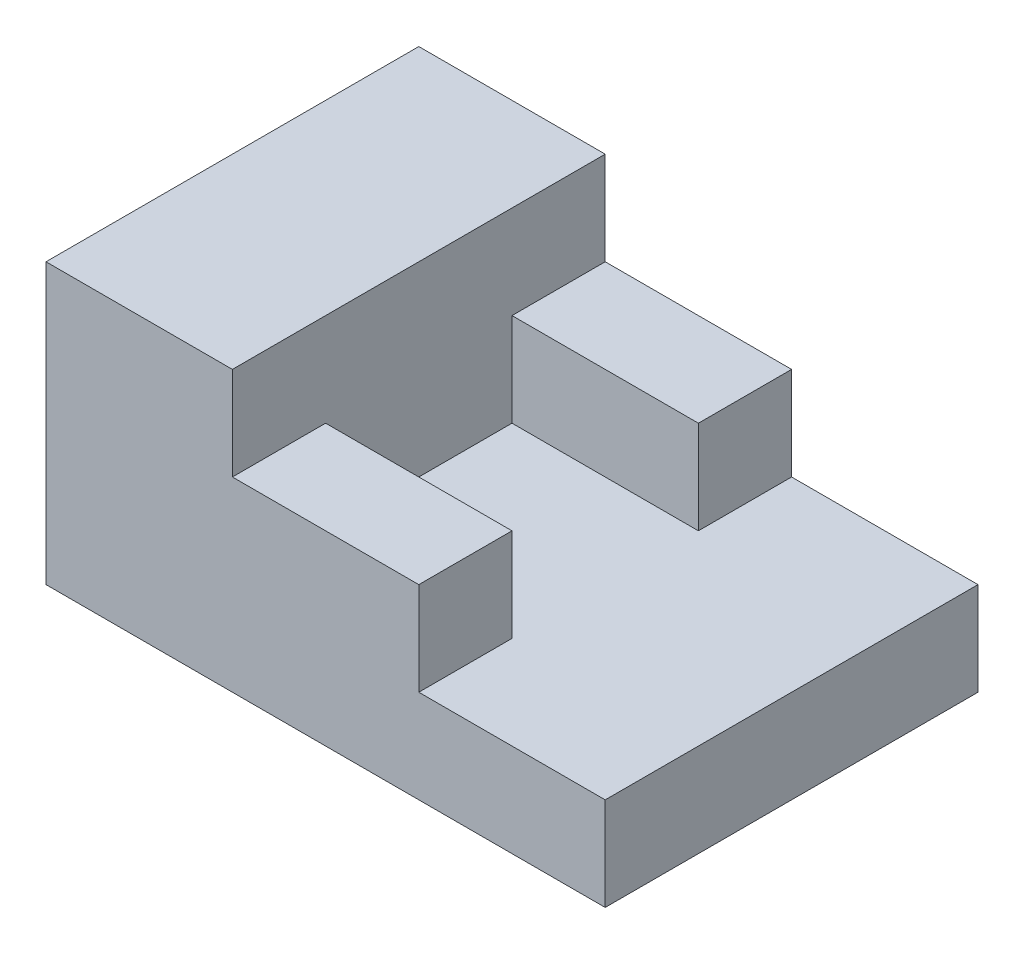
SolidWorks part; units mm, degrees
ref_plane "前基準面" through (0, 0, 0) normal (0, 0, 1) x (1, 0, 0)
ref_plane "上基準面" through (0, 0, 0) normal (0, 1, 0) x (1, 0, 0)
ref_plane "右基準面" through (0, 0, 0) normal (1, 0, 0) x (0, 0, -1)
sketch "草圖1" plane through (0, 0, 0) normal (0, 0, 1) x (1, 0, 0)
  line L0 (0, 0) -> (0, 10)
  line L1 (0, 10) -> (-20, 10)
  line L2 (-20, 10) -> (-20, -20)
  line L3 (-20, -20) -> (40, -20)
  line L4 (40, -20) -> (40, -10)
  line L5 (40, -10) -> (20, -10)
  line L6 (20, -10) -> (20, 0)
  line L7 (20, 0) -> (0, 0)
  point P8 (0, 0)
  point P11 (0, 0)
  dimension "D1" = 20
  dimension "D2" = 20
  dimension "D3" = 20
  dimension "D4" = 10
  dimension "D5" = 10
  dimension "D6" = 10
extrude "填料-伸長1" add sketch "草圖1" along normal blind 40
sketch "草圖2" plane through (0, 0, 0) normal (0, 1, 0) x (1, 0, 0)
  line L0 (0, -10) -> (20, -10)
  line L1 (0, -40) -> (0, 0) construction
  line L2 (20, -40) -> (20, 0) construction
  line L3 (20, -10) -> (20, 0)
  line L4 (20, 0) -> (40, 0)
  line L5 (40, 0) -> (40, -40)
  line L6 (40, -40) -> (20, -40)
  line L7 (20, -40) -> (20, -30)
  line L8 (20, -40) -> (20, 0) construction
  line L9 (20, -30) -> (0, -30)
  line L10 (0, -30) -> (0, -10)
  dimension "D1" = 20
  dimension "D2" = 10
extrude "除料-伸長1" cut sketch "草圖2" against normal blind 10
